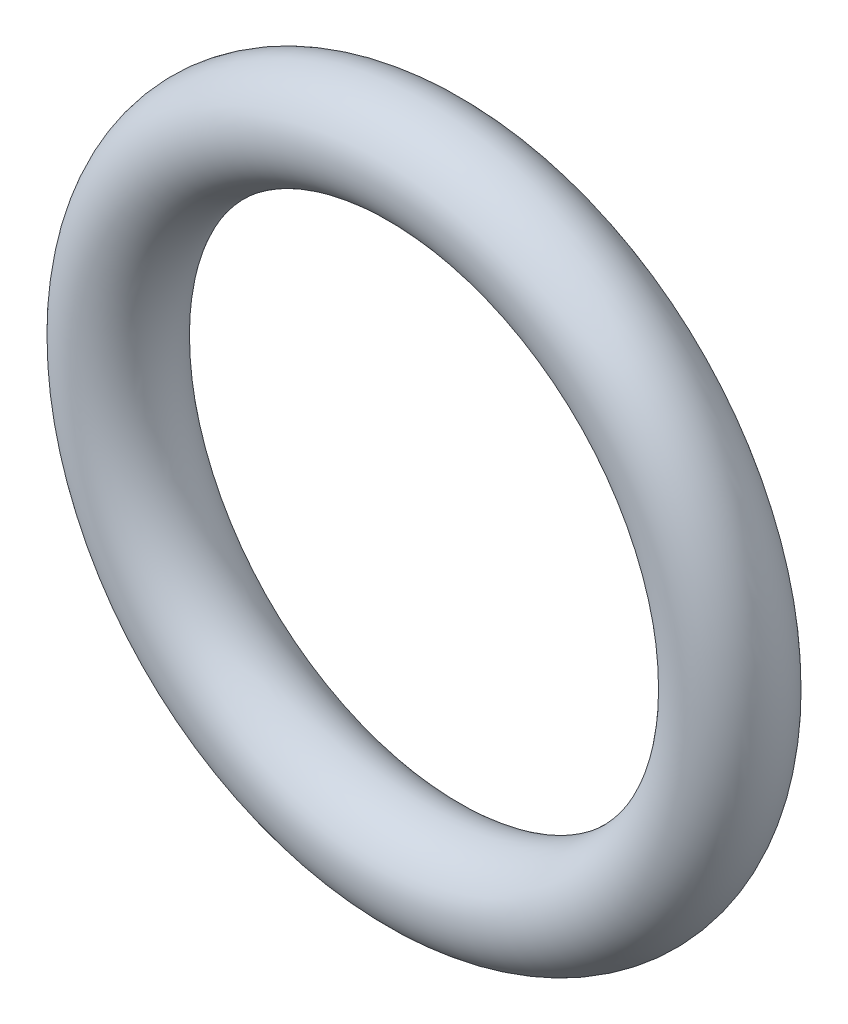
SolidWorks part; units mm, degrees
ref_plane "Front" through (0, 0, 0) normal (0, 0, 1) x (1, 0, 0)
ref_plane "Top" through (0, 0, 0) normal (0, 1, 0) x (1, 0, 0)
ref_plane "Right" through (0, 0, 0) normal (1, 0, 0) x (0, 0, -1)
sketch "Sketch1" plane through (0, 0, 0) normal (0, 0, 1) x (1, 0, 0)
  circle A0 centre (0, 0) radius 4.6228
  dimension "D1" = 9.2456
sketch "Sketch2" plane through (0, 0, 0) normal (0, 1, 0) x (1, 0, 0)
  circle A0 centre (4.6228, 0) radius 0.762
  dimension "D1" = 1.524
sweep "Base-Sweep" add profiles "Sketch2" path "Sketch1"
ref_plane "Back-Surface" through (0, 0, -0.762) normal (0, 0, 1) x (1, 0, 0)
ref_plane "Front-Surface" through (0, 0, 0.762) normal (0, 0, 1) x (1, 0, 0)
